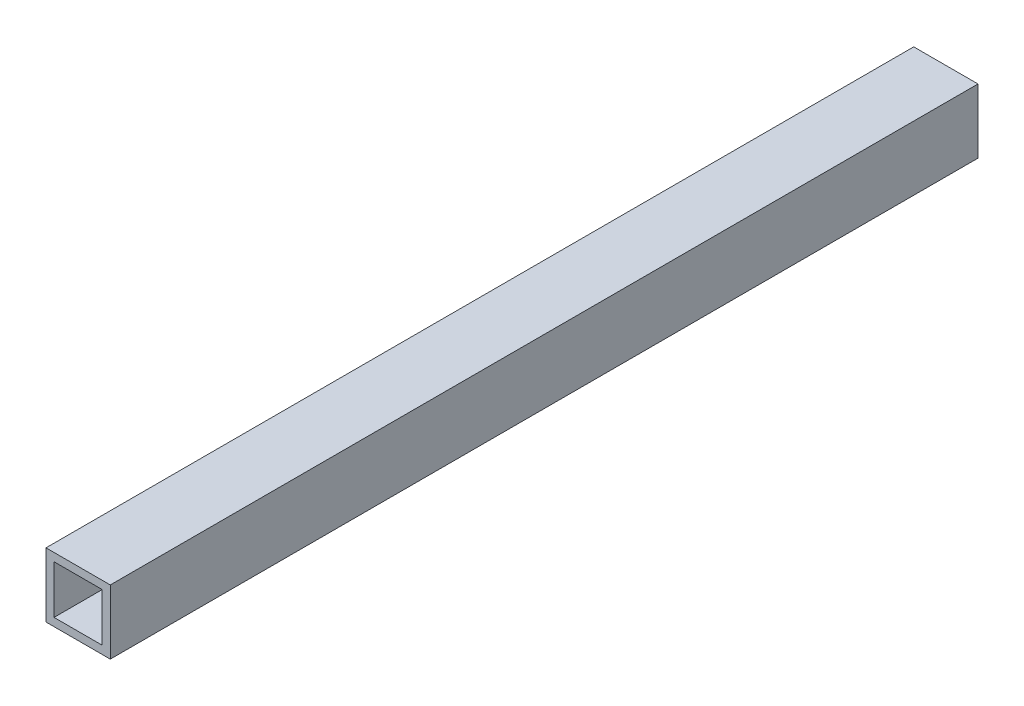
SolidWorks part; units mm, degrees
ref_plane "Front Plane" through (0, 0, 0) normal (0, 0, 1) x (1, 0, 0)
ref_plane "Top Plane" through (0, 0, 0) normal (0, 1, 0) x (1, 0, 0)
ref_plane "Right Plane" through (0, 0, 0) normal (1, 0, 0) x (0, 0, -1)
sketch "Sketch1" plane through (0, 0, 0) normal (0, 0, 1) x (1, 0, 0)
  line L0 (3.175, 22.225) -> (22.225, 22.225)
  line L1 (0, 0) -> (25.4, 0)
  line L2 (0, 0) -> (0, 25.4)
  line L3 (0, 25.4) -> (25.4, 25.4)
  line L4 (25.4, 0) -> (25.4, 25.4)
  line L5 (22.225, 3.175) -> (22.225, 22.225)
  line L6 (3.175, 3.175) -> (22.225, 3.175)
  line L7 (3.175, 3.175) -> (3.175, 22.225)
  dimension "D1" = 25.4
  dimension "D2" = 25.4
  dimension "D3" = 3.175
extrude "Boss-Extrude1" add sketch "Sketch1" along normal blind 342.9
